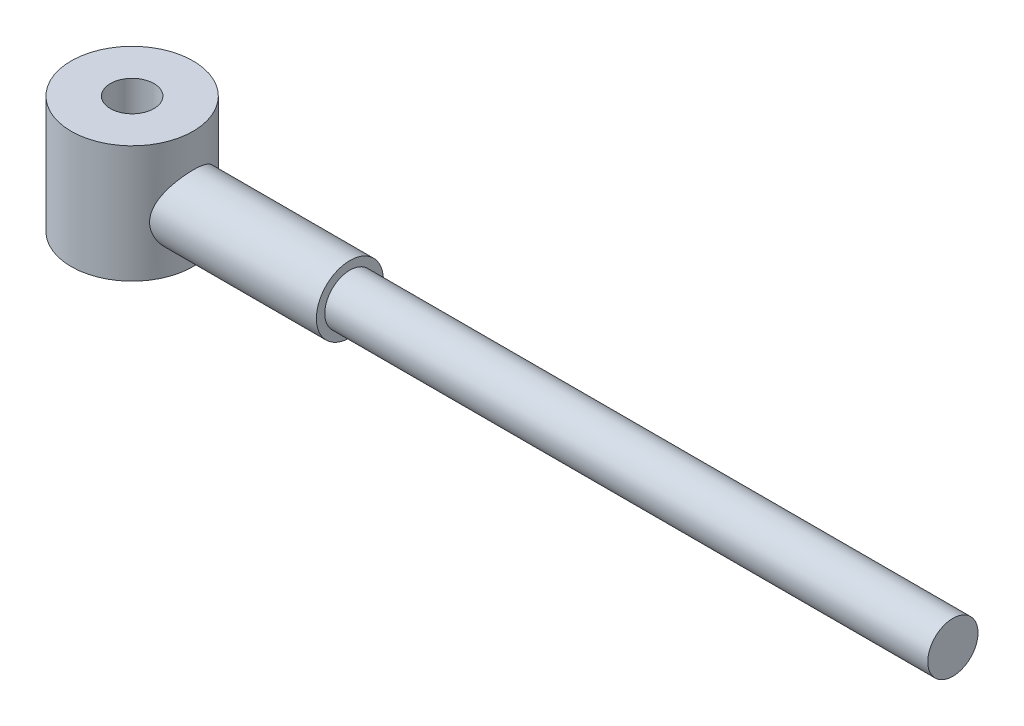
SolidWorks part; units mm, degrees
ref_plane "Alzado" through (0, 0, 0) normal (0, 0, 1) x (1, 0, 0)
ref_plane "Planta" through (0, 0, 0) normal (0, 1, 0) x (1, 0, 0)
ref_plane "Vista lateral" through (0, 0, 0) normal (1, 0, 0) x (0, 0, -1)
sketch "Sketch1" plane through (0, 0, 0) normal (0, 0, 1) x (1, 0, 0)
  line L1 (0, 0) -> (180, 0)
  line L3 (0, 7.5) -> (180, 7.5)
  line L4 (180, 0) -> (180, 7.5)
  line L5 (0, 0) -> (-50, 0)
  line L6 (0, 7.5) -> (0, 10)
  line L7 (0, 10) -> (-50, 10)
  line L8 (-50, 0) -> (-50, 10)
  dimension "D1" = 180
  dimension "D2" = 50
  dimension "D3" = 10
  dimension "D4" = 7.5
revolve "Revolve1" add sketch "Sketch1" angle 360 about L5
sketch "Sketch2" plane through (0, 0, 0) normal (0, 1, 0) x (1, 0, 0)
  line L0 (-50, 10) -> (-50, -10) construction
  circle A0 centre (-65, 0) radius 18.2
  dimension "D1" = 36.4
  dimension "D2" = 15
extrude "Boss-Extrude1" add sketch "Sketch2" along normal blind 20 and the other way blind 15
sketch "Sketch3" plane through (0, 20, 0) normal (0, 1, 0) x (1, 0, 0)
  circle A0 centre (-65, 0) radius 6.5
  dimension "D1" = 13
extrude "Cut-Extrude1" cut sketch "Sketch3" against normal blind 55
